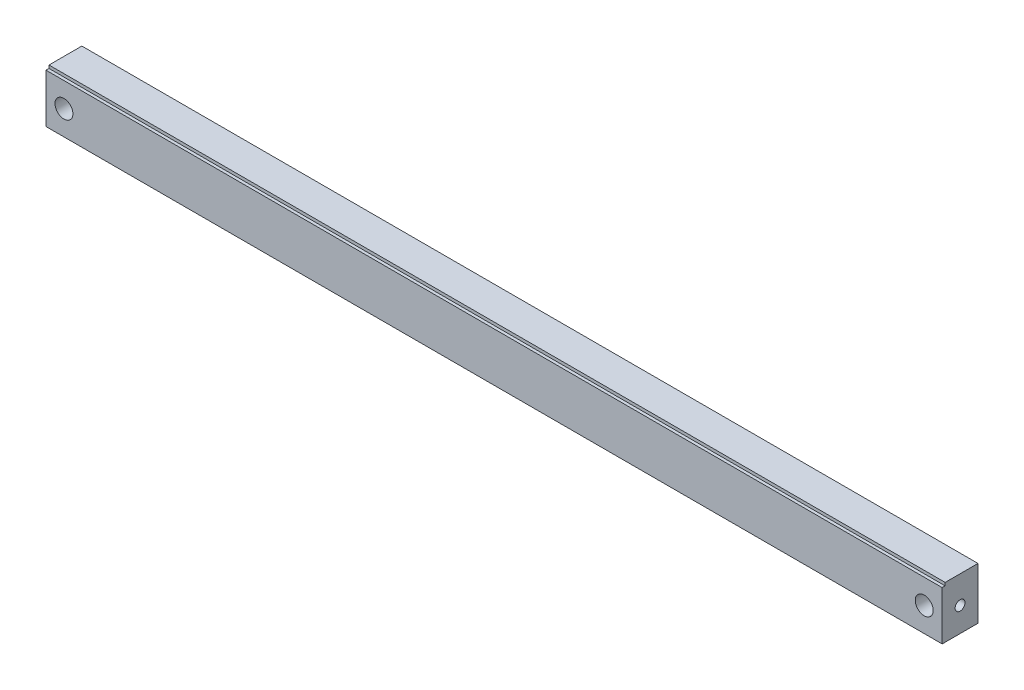
SolidWorks part; units mm, degrees
material "3.1355 (EN-AW 2024)"
ref_plane "Спереди" through (0, 0, 0) normal (0, 0, 1) x (1, 0, 0)
ref_plane "Сверху" through (0, 0, 0) normal (0, 1, 0) x (1, 0, 0)
ref_plane "Справа" through (0, 0, 0) normal (1, 0, 0) x (0, 0, -1)
sketch "Эскиз1" plane through (0, 0, 0) normal (0, 1, 0) x (1, 0, 0)
  line L1 (-150, 12) -> (150, 12)
  line L2 (-150, 12) -> (-150, 0)
  line L3 (-150, 0) -> (150, 0)
  line L4 (150, 12) -> (150, 0)
  point P4 (0, 0)
  dimension "D1" = 300
  dimension "D2" = 12
extrude "База" add sketch "Эскиз1" along normal blind 17.35
sketch "Эскиз2" plane through (0, 17.35, 0) normal (0, 1, 0) x (1, 0, 0)
  line L0 (150, 0) -> (150, 12) construction
  line L1 (-150, 0) -> (150, 0)
  line L2 (-150, 0) -> (-150, 1)
  line L3 (-150, 1) -> (150, 1)
  line L4 (150, 0) -> (150, 1)
  dimension "D1" = 1
extrude "Вырез-Вытянуть1" cut sketch "Эскиз2" against normal blind 1
sketch "Эскиз5" plane through (0, 0, 0) normal (0, 0, 1) x (1, 0, 0)
  line L1 (-144, 8.175) -> (-150, 8.175) construction
  line L2 (144, 8.175) -> (150, 8.175) construction
  line L4 (150, 16.35) -> (150, 0) construction
  line L5 (-150, 16.35) -> (-150, 0) construction
  circle A0 centre (-144, 8.175) radius 3
  circle A1 centre (144, 8.175) radius 3
  point P12 (-150, 8.175)
  dimension "D1" = 6
  dimension "D2" = 6
  dimension "D3" = 0
extrude "Валы-6мм" cut sketch "Эскиз5" against normal through all
hole_wizard "Фиксация-M4" positions "Эскиз8" profile "Эскиз10" tap size "M4" standard "DIN"
sketch "Эскиз8" plane through (150, 0, 0) normal (1, 0, 0) x (0, 0, -1)
  line L0 (6, 8.175) -> (6, 11.175) construction
  line L1 (12, 11.175) -> (0, 11.175) construction
  line L4 (6, 8.175) -> (6, 5.175) construction
  line L5 (0, 5.175) -> (12, 5.175) construction
  point P0 (6, 8.175)
sketch "Эскиз10" plane through (150, 8.175, -6) normal (0, 1, 0) x (0, 0, -1)
  line L0 (0, 0) -> (0, 10.9914)
  line L1 (0, 10.9914) -> (1.65, 10)
  line L2 (1.65, 10) -> (1.65, 0)
  line L5 (1.65, 0) -> (0, 0)
  line L10 (0, 10.9914) -> (-1.65, 10) construction
  line L11 (0, -6.35) -> (0, 107.95) construction
  dimension "Диаметр сверла" = 3.3
  dimension "Глубина сверла" = 10
  dimension "Угол заточки сверла" = 118
cosmetic thread "Отверстие резьбы2" parameters "D1"=2.3562, "D2"=4
mirror "Зеркальное отражение1" about plane through (0, 0, 0) normal (1, 0, 0) of "Фиксация-M4"
